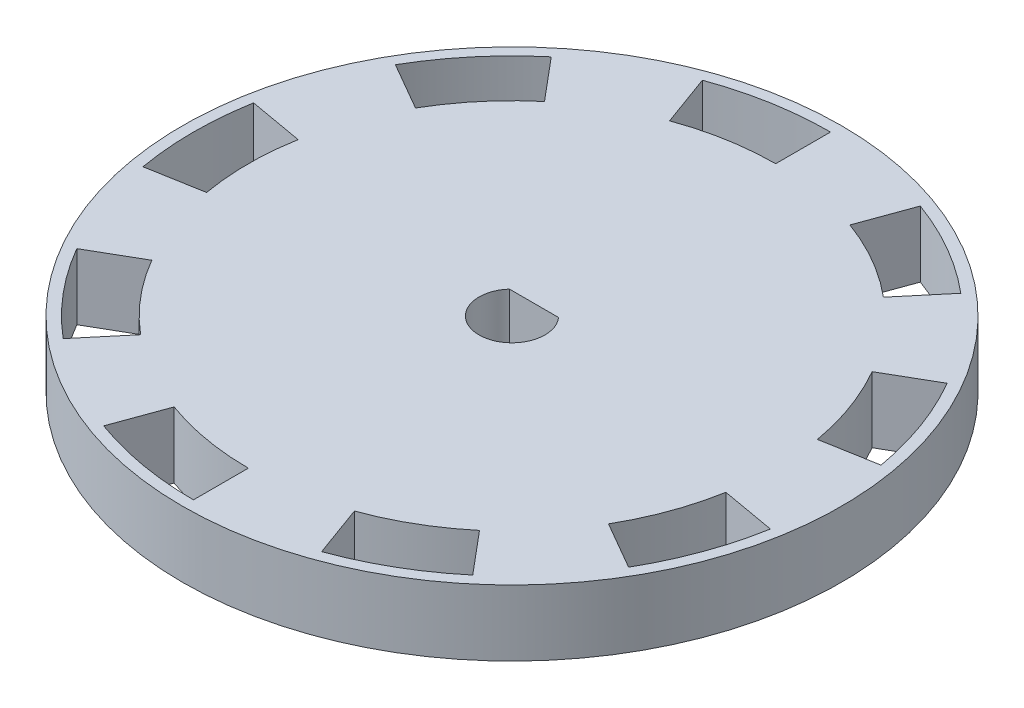
SolidWorks part; units mm, degrees
ref_plane "Front Plane" through (0, 0, 0) normal (0, 0, 1) x (1, 0, 0)
ref_plane "Top Plane" through (0, 0, 0) normal (0, 1, 0) x (1, 0, 0)
ref_plane "Right Plane" through (0, 0, 0) normal (1, 0, 0) x (0, 0, -1)
sketch "Sketch1" plane through (0, 0, 0) normal (0, 1, 0) x (1, 0, 0)
  line L0 (-4.9593, 13.6255) -> (-4.1042, 11.2763)
  line L1 (0, 14.5) -> (0, 12)
  line L18 (10.3923, 6) -> (12.5574, 7.25)
  line L19 (7.7135, 9.1925) -> (9.3204, 11.1076)
  line L20 (4.1042, 11.2763) -> (4.9593, 13.6255)
  line L23 (-7.7135, 9.1925) -> (-9.3204, 11.1076)
  line L24 (-10.3923, 6) -> (-12.5574, 7.25)
  line L25 (-11.8177, 2.0838) -> (-14.2797, 2.5179)
  line L26 (-11.8177, -2.0838) -> (-14.2797, -2.5179)
  line L27 (-10.3923, -6) -> (-12.5574, -7.25)
  line L28 (-7.7135, -9.1925) -> (-9.3204, -11.1076)
  line L29 (-4.1042, -11.2763) -> (-4.9593, -13.6255)
  line L30 (0, -12) -> (0, -14.5)
  line L31 (4.1042, -11.2763) -> (4.9593, -13.6255)
  line L32 (7.7135, -9.1925) -> (9.3204, -11.1076)
  line L33 (10.3923, -6) -> (12.5574, -7.25)
  line L34 (11.8177, -2.0838) -> (14.2797, -2.5179)
  line L35 (11.8177, 2.0838) -> (14.2797, 2.5179)
  line L47 (-1.118, 1) -> (1.118, 1)
  circle A0 centre (0, 0) radius 15
  arc A1 (0, 14.5) -> (-4.9593, 13.6255) centre (0, 0) ccw
  arc A2 (7.7135, 9.1925) -> (4.1042, 11.2763) centre (0, 0) ccw
  arc A3 (11.8177, 2.0838) -> (10.3923, 6) centre (0, 0) ccw
  arc A4 (9.3204, 11.1076) -> (4.9593, 13.6255) centre (0, 0) ccw
  arc A5 (10.3923, -6) -> (11.8177, -2.0838) centre (0, 0) ccw
  arc A6 (14.2797, 2.5179) -> (12.5574, 7.25) centre (0, 0) ccw
  arc A7 (4.1042, -11.2763) -> (7.7135, -9.1925) centre (0, 0) ccw
  arc A8 (12.5574, -7.25) -> (14.2797, -2.5179) centre (0, 0) ccw
  arc A9 (-4.1042, -11.2763) -> (0, -12) centre (0, 0) ccw
  arc A10 (4.9593, -13.6255) -> (9.3204, -11.1076) centre (0, 0) ccw
  arc A11 (-10.3923, -6) -> (-7.7135, -9.1925) centre (0, 0) ccw
  arc A12 (-4.9593, -13.6255) -> (0, -14.5) centre (0, 0) ccw
  arc A13 (-11.8177, 2.0838) -> (-11.8177, -2.0838) centre (0, 0) ccw
  arc A14 (-12.5574, -7.25) -> (-9.3204, -11.1076) centre (0, 0) ccw
  arc A15 (-7.7135, 9.1925) -> (-10.3923, 6) centre (0, 0) ccw
  arc A16 (-14.2797, 2.5179) -> (-14.2797, -2.5179) centre (0, 0) ccw
  circle A17 centre (0, 0) radius 10
  arc A18 (-9.3204, 11.1076) -> (-12.5574, 7.25) centre (0, 0) ccw
  arc A19 (0, 12) -> (-4.1042, 11.2763) centre (0, 0) ccw
  circle A38 centre (0, 0) radius 4
  circle A39 centre (0, 0) radius 1.5
  point P26 (0, 0)
  point P44 (0, 0)
  point P92 (0, 0)
  point P98 (0, 0)
  point P116 (0, 0)
  dimension "D1" = 30
  dimension "D2" = 29
  dimension "D3" = 20
  dimension "D6" = 8
  dimension "D10" = 3
  dimension "D9" = 24
  dimension "D11" = 1
extrude "Boss-Extrude1" add sketch "Sketch1" along normal blind 3
